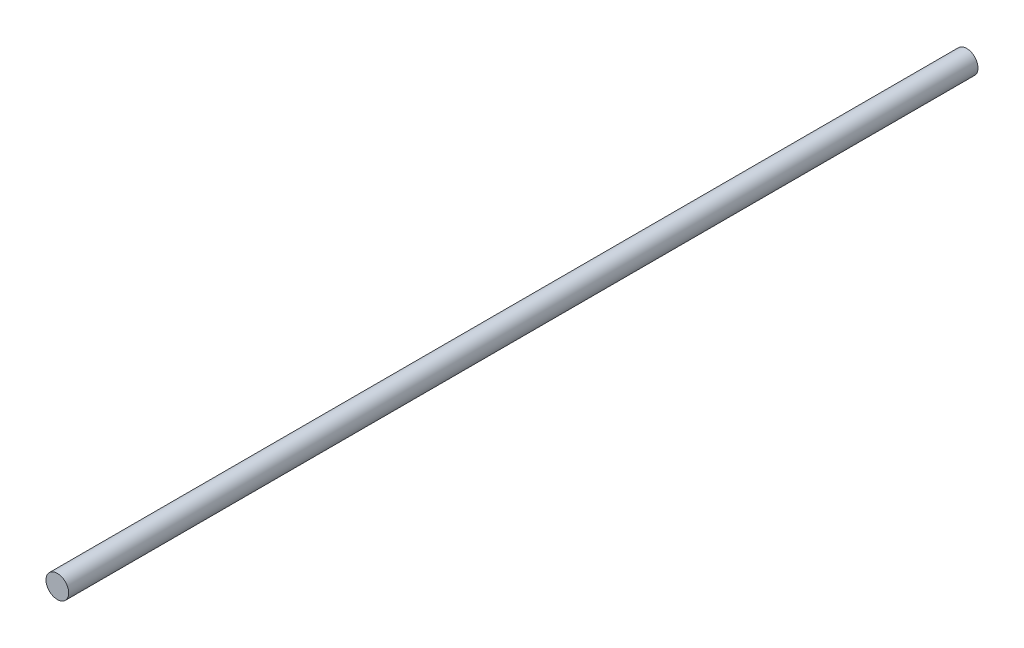
SolidWorks part; units mm, degrees
ref_plane "Plan de face" through (0, 0, 0) normal (0, 0, 1) x (1, 0, 0)
ref_plane "Plan de dessus" through (0, 0, 0) normal (0, 1, 0) x (1, 0, 0)
ref_plane "Plan de droite" through (0, 0, 0) normal (1, 0, 0) x (0, 0, -1)
sketch "Esquisse1" plane through (0, 0, 0) normal (0, 0, 1) x (1, 0, 0)
  circle A0 centre (0, 0) radius 1.5
  dimension "D1" = 3
extrude "Boss.-Extru.1" add sketch "Esquisse1" along normal blind 120
cosmetic thread "Représentation de filetage1" parameters "D1"=10, "D2"=2.439
cosmetic thread "Représentation de filetage2" parameters "D1"=10, "D2"=2.439
